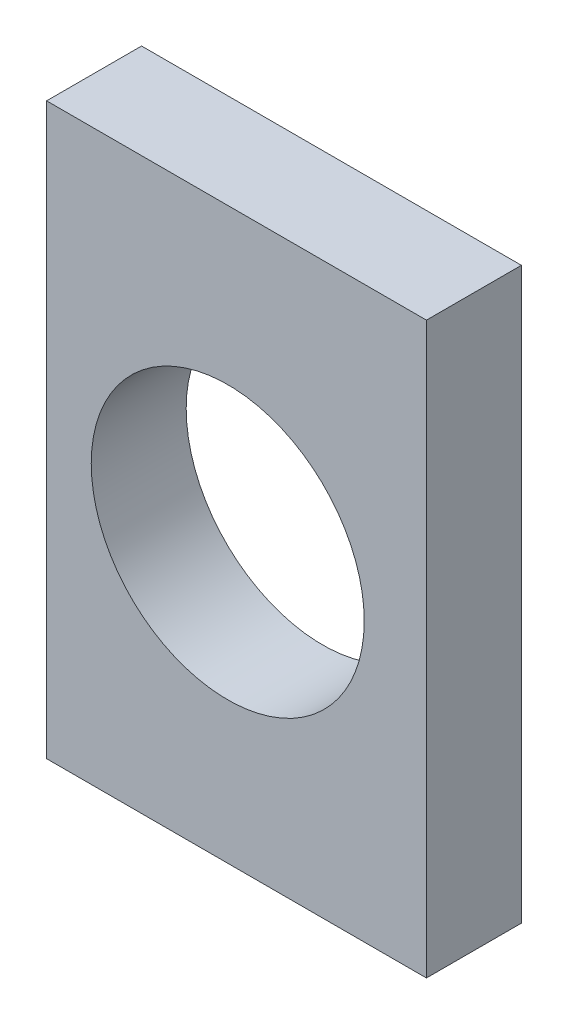
SolidWorks part; units mm, degrees
ref_plane "Front Plane" through (0, 0, 0) normal (0, 0, 1) x (1, 0, 0)
ref_plane "Top Plane" through (0, 0, 0) normal (0, 1, 0) x (1, 0, 0)
ref_plane "Right Plane" through (0, 0, 0) normal (1, 0, 0) x (0, 0, -1)
sketch "Sketch1" plane through (0, 0, 0) normal (0, 0, 1) x (1, 0, 0)
  line L1 (-1.75, 17.5) -> (14.25, 17.5)
  line L2 (-1.75, 17.5) -> (-1.75, -6.5)
  line L3 (-1.75, -6.5) -> (14.25, -6.5)
  line L4 (14.25, 17.5) -> (14.25, -6.5)
  circle A0 centre (5.8797, 5.2129) radius 5.75
  dimension "D1" = 24
  dimension "D2" = 16
extrude "Boss-Extrude1" add sketch "Sketch1" along normal blind 4
